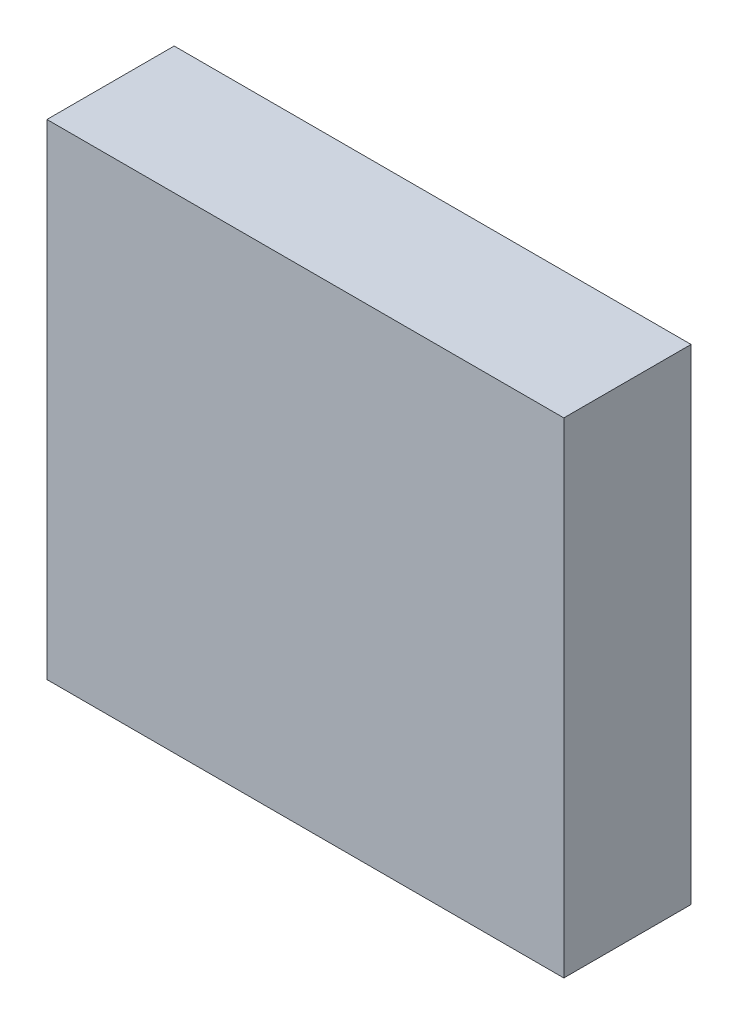
SolidWorks part; units mm, degrees
ref_plane "前视基准面" through (0, 0, 0) normal (0, 0, 1) x (1, 0, 0)
ref_plane "上视基准面" through (0, 0, 0) normal (0, 1, 0) x (1, 0, 0)
ref_plane "右视基准面" through (0, 0, 0) normal (1, 0, 0) x (0, 0, -1)
sketch "草图1" plane through (0, 0, 0) normal (0, 0, 1) x (1, 0, 0)
  line L0 (-1.625, -1.525) -> (1.625, -1.525)
  line L1 (1.625, -1.525) -> (1.625, 1.525)
  line L2 (1.625, 1.525) -> (-1.625, 1.525)
  line L3 (-1.625, 1.525) -> (-1.625, -1.525)
extrude "凸台-拉伸1" add sketch "草图1" along normal blind 0.8 from offset 0
